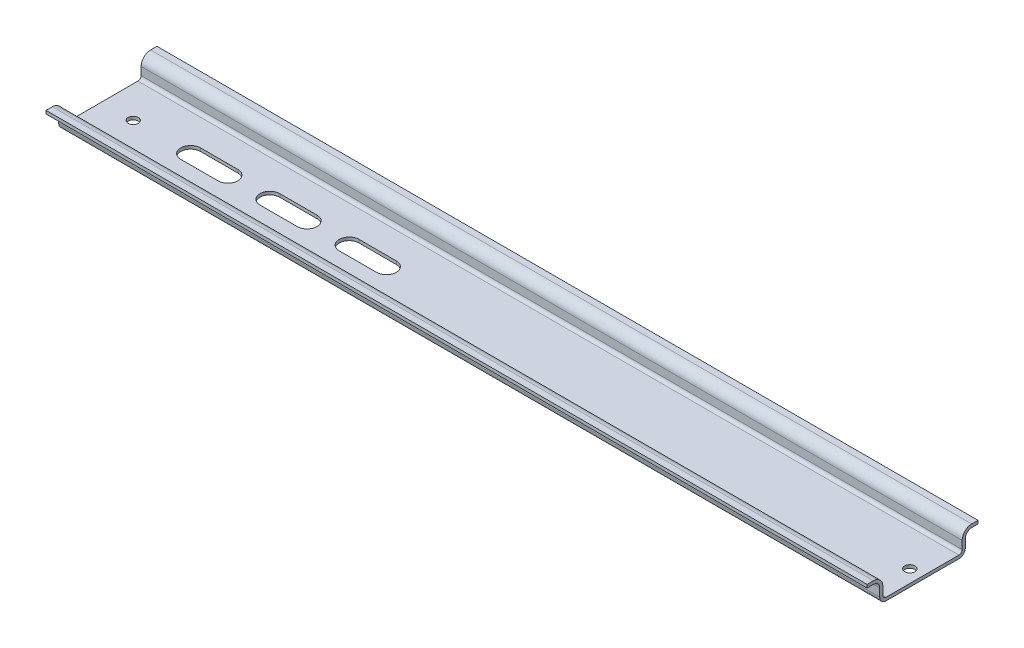
SolidWorks part; units mm, degrees
ref_plane "Front Plane" through (0, 0, 0) normal (0, 0, 1) x (1, 0, 0)
ref_plane "Top Plane" through (0, 0, 0) normal (0, 1, 0) x (1, 0, 0)
ref_plane "Right Plane" through (0, 0, 0) normal (1, 0, 0) x (0, 0, -1)
sketch "Sketch1" plane through (0, 0, 0) normal (1, 0, 0) x (0, 0, -1)
  line L0 (0, 0) -> (0, 18.2344) construction
  line L1 (0, 0) -> (26.621, 0) construction
  line L2 (-11.5, 0) -> (11.5, 0)
  line L3 (13.5, 2) -> (13.5, 4.5)
  line L4 (15.5, 6.5) -> (17.5, 6.5)
  line L5 (-13.5, 2) -> (-13.5, 4.5)
  line L6 (-15.5, 6.5) -> (-17.5, 6.5)
  arc A0 (13.5, 2) -> (11.5, 0) centre (11.5, 2) cw
  arc A1 (15.5, 6.5) -> (13.5, 4.5) centre (15.5, 4.5) ccw
  arc A2 (-13.5, 2) -> (-11.5, 0) centre (-11.5, 2) ccw
  arc A3 (-15.5, 6.5) -> (-13.5, 4.5) centre (-15.5, 4.5) cw
  point P9 (13.5, 0)
  dimension "D1" = 2
  dimension "D3" = 2
  dimension "D2" = 6.5
  dimension "D4" = 35
  dimension "D5" = 27
extrude "Extrude-Thin1" add sketch "Sketch1" along normal blind 200 and the other way blind 59 thin thin type one direction wall 1
sketch "Sketch2" plane through (0, 0, 0) normal (0, -1, 0) x (1, 0, 0)
  line L0 (0, 6.6969) -> (0, 0) construction
  line L1 (0, 0) -> (9.9599, 0) construction
  line L2 (-5.875, 3.125) -> (5.875, 3.125)
  line L3 (-5.875, -3.125) -> (5.875, -3.125)
  arc A0 (5.875, 3.125) -> (5.875, -3.125) centre (5.875, 0) cw
  arc A1 (-5.875, 3.125) -> (-5.875, -3.125) centre (-5.875, 0) ccw
  point P6 (0, 3.125)
  point P12 (0, -3.125)
  dimension "D2" = 11.75
  dimension "D1" = 6.25
extrude "Cut-Extrude1" cut sketch "Sketch2" against normal up to next
pattern_linear "LPattern1" count 2 spacing 25 along (1, 0, 0) count 2 spacing 25 along (-1, 0, 0) of "Cut-Extrude1"
sketch "Szkic1" plane through (0, 0, 0) normal (0, -1, 0) x (1, 0, 0)
  circle A0 centre (-49, 0) radius 1.6
  circle A1 centre (196, 0) radius 1.6
extrude "Wytnij-wyciągnięcie1" cut sketch "Szkic1" against normal through all
